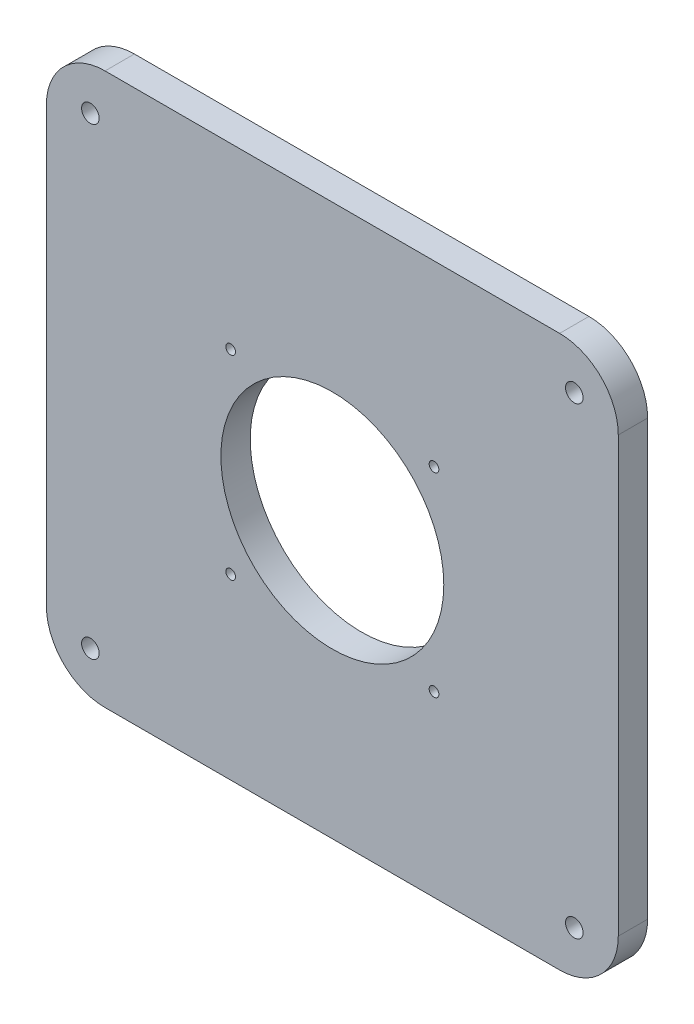
SolidWorks part; units mm, degrees
ref_plane "Front Plane" through (0, 0, 0) normal (0, 0, 1) x (1, 0, 0)
ref_plane "Top Plane" through (0, 0, 0) normal (0, 1, 0) x (1, 0, 0)
ref_plane "Right Plane" through (0, 0, 0) normal (1, 0, 0) x (0, 0, -1)
sketch "Sketch1" plane through (0, 0, 0) normal (0, 0, 1) x (1, 0, 0)
  line L0 (0, 0) -> (165, 0) construction
  line L1 (165, 0) -> (165, 158) construction
  line L2 (165, 158) -> (0, 158) construction
  line L3 (0, 158) -> (0, 0) construction
  line L4 (0, 158) -> (165, 0) construction
  line L5 (165, 158) -> (0, 0) construction
  line L7 (-15, 173) -> (180, 173)
  line L8 (-15, 173) -> (-15, -15)
  line L9 (-15, -15) -> (180, -15)
  line L10 (180, 173) -> (180, -15)
  circle A0 centre (165, 0) radius 3
  circle A1 centre (165, 158) radius 3
  circle A2 centre (0, 158) radius 3
  circle A3 centre (0, 0) radius 3
  circle A4 centre (82.5, 79) radius 38
  circle A5 centre (82.5, 79) radius 48 construction
  circle A6 centre (117.1686, 112.1978) radius 1.65
  circle A7 centre (47.8314, 112.1978) radius 1.65
  circle A8 centre (47.8314, 45.8022) radius 1.65
  circle A9 centre (117.1686, 45.8022) radius 1.65
  dimension "D3" = 6
  dimension "D4" = 76
  dimension "D9" = 96
  dimension "D10" = 3.3
  dimension "D1" = 165
  dimension "D2" = 158
  dimension "D5" = 15
  dimension "D6" = 15
  dimension "D7" = 15
  dimension "D8" = 15
extrude "Boss-Extrude1" add sketch "Sketch1" along normal blind 10
fillet "Fillet1" radius 20 4 edges at (-15, -15, 5) (180, -15, 5) (180, 173, 5) (-15, 173, 5)
